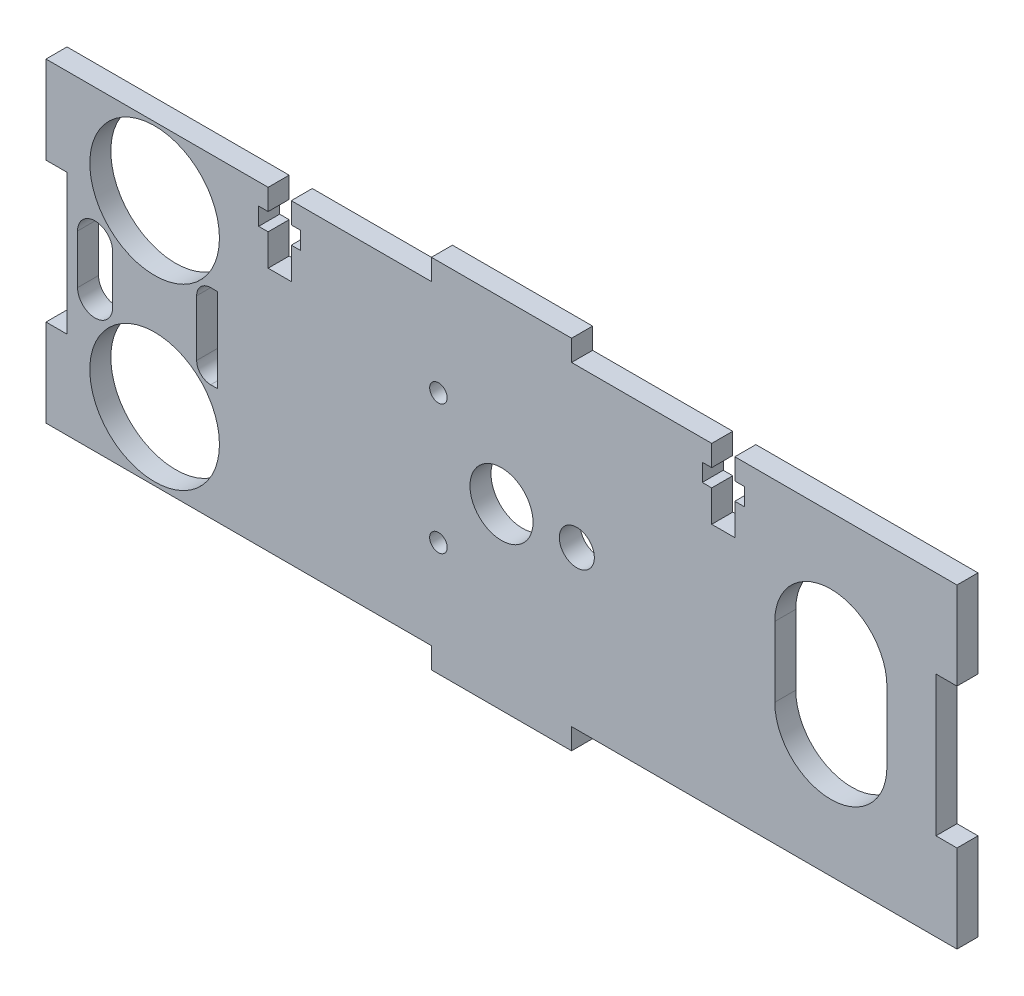
SolidWorks part; units mm, degrees
ref_plane "Front Plane" through (0, 0, 0) normal (0, 0, 1) x (1, 0, 0)
ref_plane "Top Plane" through (0, 0, 0) normal (0, 1, 0) x (1, 0, 0)
ref_plane "Right Plane" through (0, 0, 0) normal (1, 0, 0) x (0, 0, -1)
sketch "Sketch1" plane through (0, 0, 0) normal (0, 0, 1) x (1, 0, 0)
  line L0 (-10, -22.5) -> (-65, -22.5)
  line L1 (65, -22.5) -> (10, -22.5)
  line L2 (65, -22.5) -> (65, -10)
  line L3 (65, 22.5) -> (33.3, 22.5)
  line L4 (-65, -22.5) -> (-65, -10)
  line L5 (65, -22.5) -> (-65, 22.5) construction
  line L6 (65, 22.5) -> (-65, -22.5) construction
  line L8 (-10, -22.5) -> (-10, -25.5)
  line L9 (-10, -25.5) -> (10, -25.5)
  line L10 (10, -22.5) -> (10, -25.5)
  line L11 (0, -55) -> (0, 55) construction
  line L12 (-62, -10) -> (-65, -10)
  line L13 (-62, -10) -> (-62, 10)
  line L14 (-62, 10) -> (-65, 10)
  line L16 (-62, -10) -> (-65, 10) construction
  line L17 (-62, 10) -> (-65, -10) construction
  line L18 (62, 10) -> (65, 10)
  line L20 (62, -10) -> (65, -10)
  line L21 (62, -10) -> (62, 10)
  line L22 (-65, 10) -> (-65, 22.5)
  line L23 (65, 10) -> (65, 22.5)
  line L24 (-58, 3.5) -> (-58, -3.5) construction
  line L29 (-55.5, 3.5) -> (-55.5, -3.5)
  line L30 (-60.5, 3.5) -> (-60.5, -3.5)
  line L31 (-40.5, -6) -> (-41.5, -6)
  line L32 (-40.5, -6) -> (-40.5, 6)
  line L33 (-40.5, 6) -> (-41.5, 6)
  line L34 (-43.5, -4) -> (-43.5, 4)
  line L35 (-40.5, -6) -> (-43.5, 6) construction
  line L36 (-40.5, 6) -> (-43.5, -6) construction
  line L37 (55, 0) -> (-55, 0) construction
  line L40 (-10, 22.5) -> (-10, 25.5)
  line L41 (-10, 25.5) -> (10, 25.5)
  line L42 (10, 22.5) -> (10, 25.5)
  line L43 (-10, 22.5) -> (-30, 22.5)
  line L44 (33.3, 12.5) -> (30, 12.5)
  line L46 (-33.3, 22.5) -> (-33.3, 19.5)
  line L47 (-33.3, 12.5) -> (-30, 12.5)
  line L48 (-30, 22.5) -> (-30, 19.5)
  line L49 (-34.65, 19.5) -> (-33.3, 19.5)
  line L50 (-34.65, 19.5) -> (-34.65, 17)
  line L51 (-34.65, 17) -> (-33.3, 17)
  line L52 (-28.65, 19.5) -> (-28.65, 17)
  line L53 (30, 22.5) -> (30, 19.5)
  line L55 (33.3, 22.5) -> (33.3, 19.5)
  line L56 (34.65, 17) -> (33.3, 17)
  line L57 (28.65, 19.5) -> (28.65, 17)
  line L58 (34.65, 19.5) -> (33.3, 19.5)
  line L59 (34.65, 19.5) -> (34.65, 17)
  line L60 (-33.3, 22.5) -> (-65, 22.5)
  line L61 (-30, 19.5) -> (-28.65, 19.5)
  line L62 (-33.3, 17) -> (-33.3, 12.5)
  line L63 (-30, 17) -> (-28.65, 17)
  line L64 (-30, 17) -> (-30, 12.5)
  line L65 (30, 22.5) -> (10, 22.5)
  line L66 (30, 19.5) -> (28.65, 19.5)
  line L67 (30, 17) -> (30, 12.5)
  line L68 (33.3, 17) -> (33.3, 12.5)
  line L69 (30, 17) -> (28.65, 17)
  line L70 (47, -5) -> (47, 5) construction
  line L75 (39, -5) -> (39, 5)
  line L76 (55, -5) -> (55, 5)
  circle A0 centre (-49.5, 12.75) radius 9.25
  circle A1 centre (-49.5, -12.75) radius 9.25
  circle A6 centre (0, 0) radius 4.5
  circle A7 centre (10.75, 0) radius 2.5
  arc A10 (-55.5, 3.5) -> (-60.5, 3.5) centre (-58, 3.5) ccw
  arc A11 (-60.5, -3.5) -> (-55.5, -3.5) centre (-58, -3.5) ccw
  arc A12 (-41.5, -6) -> (-43.5, -4) centre (-41.5, -4) cw
  arc A13 (-41.5, 6) -> (-43.5, 4) centre (-41.5, 4) ccw
  circle A14 centre (-9, 9.25) radius 1.25
  circle A15 centre (-9, -9.25) radius 1.25
  arc A16 (39, -5) -> (55, -5) centre (47, -5) ccw
  arc A17 (55, 5) -> (39, 5) centre (47, 5) ccw
  point P0 (0, 0)
  point P10 (-63.5, 0)
  point P26 (-58, 0)
  point P49 (-42, 0)
  point P83 (47, 0)
  dimension "D8" = 18.5
  dimension "D15" = 2
  dimension "D16" = 9
  dimension "D17" = 5
  dimension "D22" = 2.5
  dimension "D12" = 2.5
  dimension "D35" = 8
  dimension "D1" = 130
  dimension "D2" = 45
  dimension "D3" = 3
  dimension "D4" = 20
  dimension "D5" = 55
  dimension "D6" = 20
  dimension "D7" = 3
  dimension "D9" = 15.5
  dimension "D10" = 25.5
  dimension "D11" = 12.75
  dimension "D13" = 7
  dimension "D14" = 6
  dimension "D18" = 10.75
  dimension "D19" = 3
  dimension "D20" = 12
  dimension "D21" = 6
  dimension "D23" = 9
  dimension "D24" = 9.25
  dimension "D25" = 20
  dimension "D26" = 3
  dimension "D27" = 55
  dimension "D28" = 3.3
  dimension "D29" = 10
  dimension "D30" = 2.5
  dimension "D31" = 6
  dimension "D32" = 3
  dimension "D33" = 1.35
  dimension "D34" = 20
  dimension "D36" = 10
  dimension "D37" = 10
extrude "Boss-Extrude1" add sketch "Sketch1" along normal blind 3
